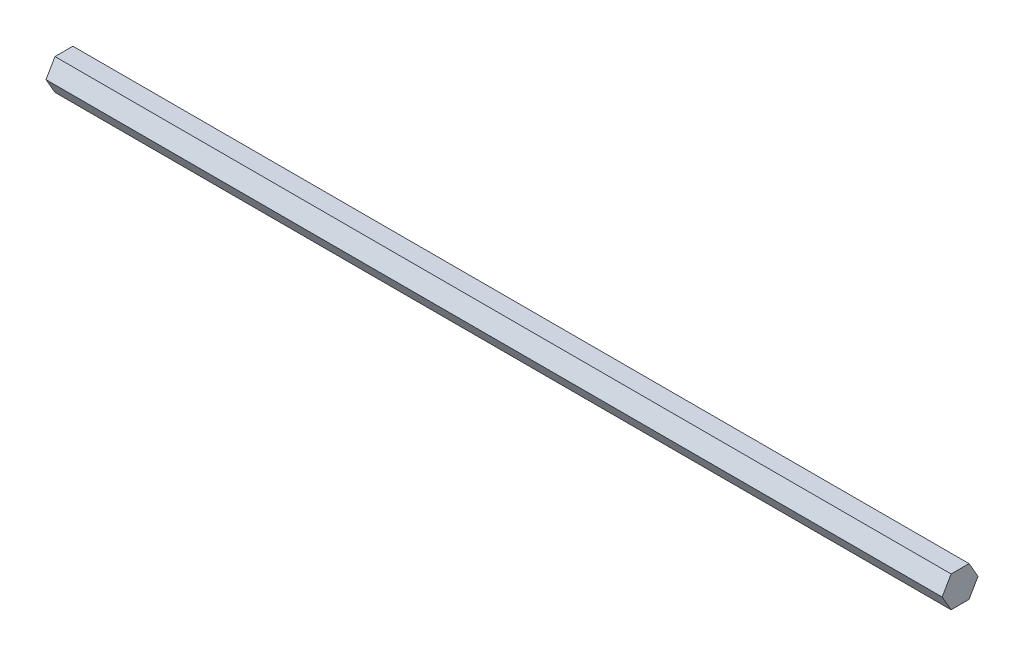
SolidWorks part; units mm, degrees
ref_plane "Front Plane" through (0, 0, 0) normal (0, 0, 1) x (1, 0, 0)
ref_plane "Top Plane" through (0, 0, 0) normal (0, 1, 0) x (1, 0, 0)
ref_plane "Right Plane" through (0, 0, 0) normal (1, 0, 0) x (0, 0, -1)
sketch "Sketch2" plane through (0, 0, 0) normal (1, 0, 0) x (0, 0, -1)
  line L1 (-6.3512, 10.9978) -> (-12.7, -0.0014)
  line L2 (-12.7, -0.0014) -> (-6.3488, -10.9992)
  line L3 (-6.3488, -10.9992) -> (6.3512, -10.9978)
  line L4 (6.3512, -10.9978) -> (12.7, 0.0014)
  line L5 (12.7, 0.0014) -> (6.3488, 10.9992)
  line L6 (6.3488, 10.9992) -> (-6.3512, 10.9978)
  circle A0 centre (0, 0) radius 10.9985 construction
  dimension "D1" = 12.7
extrude "Boss-Extrude1" add sketch "Sketch2" along normal blind 635
